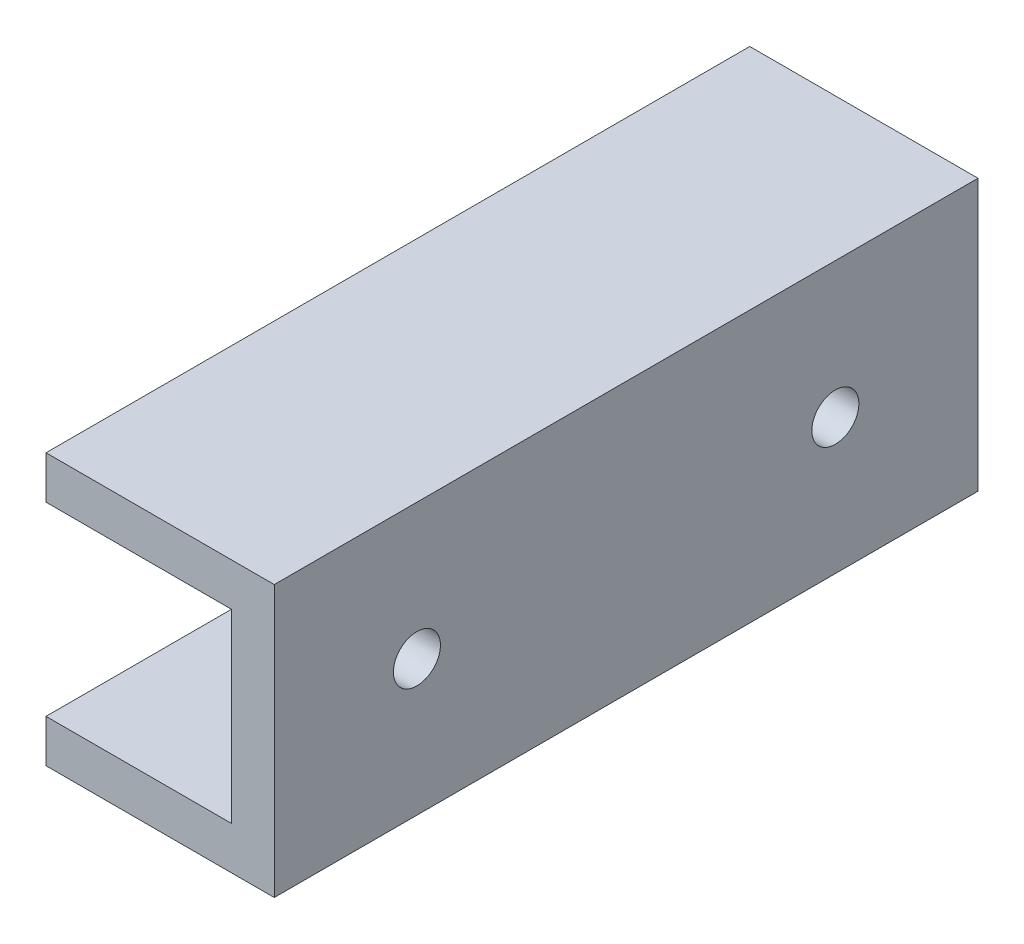
SolidWorks part; units mm, degrees
ref_plane "前视基准面" through (0, 0, 0) normal (0, 0, 1) x (1, 0, 0)
ref_plane "上视基准面" through (0, 0, 0) normal (0, 1, 0) x (1, 0, 0)
ref_plane "右视基准面" through (0, 0, 0) normal (1, 0, 0) x (0, 0, -1)
sketch "草图1" plane through (0, 0, 0) normal (0, 0, 1) x (1, 0, 0)
  line L1 (0, 0) -> (13, 0)
  line L2 (0, 0) -> (0, 13)
  line L3 (0, 13) -> (13, 13)
  line L4 (13, 0) -> (13, 13)
  dimension "D1" = 13
  dimension "D2" = 13
extrude "拉伸-薄壁1" add sketch "草图1" along normal blind 49.33 thin
sketch "草图2" plane through (-3, 0, 0) normal (-1, 0, 0) x (0, 0, 1)
  line L0 (0, 16) -> (0, -3) construction
  line L1 (49.33, 16) -> (49.33, -3) construction
  circle A0 centre (10, 6.5) radius 1.65
  circle A1 centre (39.33, 6.5) radius 1.65
  dimension "D1" = 3.3
  dimension "D2" = 3.3
  dimension "D3" = 10
  dimension "D4" = 10
extrude "切除-拉伸1" cut sketch "草图2" against normal blind 30
sketch "草图3" plane through (-3, 0, 0) normal (-1, 0, 0) x (0, 0, 1)
  line L1 (-5.2954, 23.3125) -> (111.6198, 23.3125)
  line L2 (-5.2954, 23.3125) -> (-5.2954, -22.907)
  line L3 (-5.2954, -22.907) -> (111.6198, -22.907)
  line L4 (111.6198, 23.3125) -> (111.6198, -22.907)
extrude "切除-拉伸2" cut sketch "草图3" against normal blind 3
sketch "草图4" plane through (13, 0, 0) normal (-1, 0, 0) x (0, 0, 1)
  line L0 (49.33, 13) -> (0, 13) construction
  line L1 (23, 13) -> (28, 13)
  line L2 (23, 13) -> (23, 0)
  line L3 (23, 0) -> (28, 0)
  line L4 (28, 13) -> (28, 0)
  line L5 (49.33, 0) -> (0, 0) construction
  line L6 (49.33, 13) -> (0, 13) construction
  line L7 (21.33, 13) -> (26.33, 13)
  line L8 (21.33, 13) -> (21.33, 0)
  line L9 (21.33, 0) -> (26.33, 0)
  line L10 (26.33, 13) -> (26.33, 0)
  line L11 (49.33, 0) -> (0, 0) construction
  line L12 (49.33, 0) -> (49.33, 13) construction
  line L13 (0, 0) -> (0, 13) construction
  dimension "D1" = 23
  dimension "D2" = 23
  dimension "D3" = 5
  dimension "D4" = 5
extrude "凸台-拉伸1" [suppressed] add sketch "草图4" along normal blind 10
sketch "草图5" [suppressed] plane through (13, 0, 0) normal (-1, 0, 0) x (0, 0, 1)
  line L0 (28, 0) -> (28, 13) construction
  line L1 (28, 9) -> (31.3, 9)
  line L2 (28, 9) -> (28, 4)
  line L3 (28, 4) -> (31.3, 4)
  line L4 (31.3, 9) -> (31.3, 4)
  line L5 (31.3, 13) -> (31.3, 0) construction
  line L6 (49.3, 0) -> (0, 0) construction
  dimension "D1" = 5
  dimension "D2" = 4
extrude "凸台-拉伸2" [suppressed] add sketch "草图5" along normal blind 10
sketch "草图6" [suppressed] plane through (13, 0, 0) normal (-1, 0, 0) x (0, 0, 1)
  line L1 (23, 13) -> (36.3, 13)
  line L2 (23, 13) -> (23, 0)
  line L3 (23, 0) -> (36.3, 0)
  line L4 (36.3, 13) -> (36.3, 0)
extrude "凸台-拉伸3" [suppressed] add sketch "草图6" along normal blind 10
sketch "草图7" [suppressed] plane through (3, 0, 0) normal (-1, 0, 0) x (0, 0, 1)
  line L0 (23, 13) -> (23, 0) construction
  line L1 (23, 9) -> (36.3, 9)
  line L2 (23, 9) -> (23, 4)
  line L3 (23, 4) -> (36.3, 4)
  line L4 (36.3, 9) -> (36.3, 4)
  line L5 (36.3, 0) -> (36.3, 13) construction
  line L6 (49.3, 13) -> (0, 13) construction
  dimension "D1" = 5
  dimension "D2" = 4
extrude "凸台-拉伸4" [suppressed] add sketch "草图7" along normal blind 3
sketch "草图8" [suppressed] plane through (3, 0, 0) normal (-1, 0, 0) x (0, 0, 1)
  line L0 (23, 13) -> (23, 0) construction
  line L1 (23, 9) -> (36.3, 9)
  line L2 (23, 9) -> (23, 4)
  line L3 (23, 4) -> (36.3, 4)
  line L4 (36.3, 9) -> (36.3, 4)
  line L5 (36.3, 0) -> (36.3, 13) construction
  line L6 (49.3, 13) -> (0, 13) construction
  dimension "D1" = 5
  dimension "D2" = 4
extrude "切除-拉伸3" [suppressed] cut sketch "草图8" against normal blind 3
chamfer "倒角1" [suppressed] distance 3 angle 45
chamfer "倒角2" [suppressed] distance 4 angle 45
